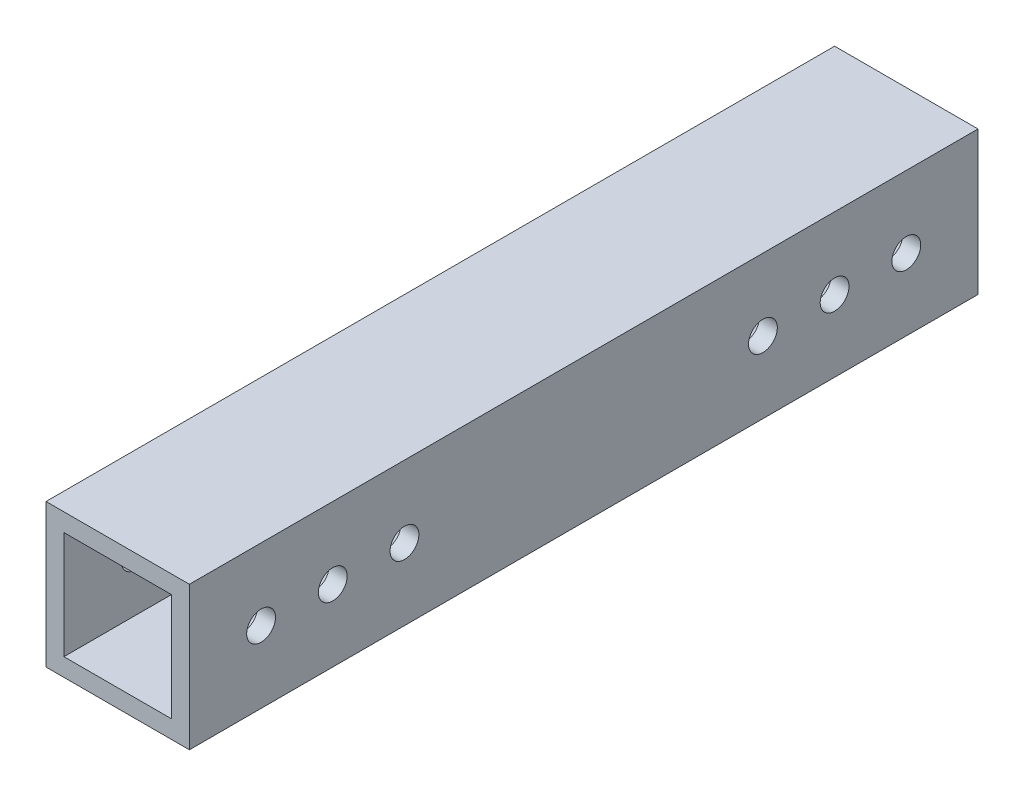
SolidWorks part; units mm, degrees
material "6061 Alloy"
ref_plane "Front" through (0, 0, 0) normal (0, 0, 1) x (1, 0, 0)
ref_plane "Top" through (0, 0, 0) normal (0, 1, 0) x (1, 0, 0)
ref_plane "Right" through (0, 0, 0) normal (1, 0, 0) x (0, 0, -1)
sketch "Sketch1" plane through (0, 0, 0) normal (0, 0, 1) x (1, 0, 0)
  line L1 (0, 0) -> (-25.4, 0)
  line L2 (0, 0) -> (0, 25.4)
  line L3 (0, 25.4) -> (-25.4, 25.4)
  line L4 (-25.4, 0) -> (-25.4, 25.4)
  dimension "D1" = 25.4
extrude "Extrude-Thin1" add sketch "Sketch1" along normal blind 139.7 thin
hole_wizard "#10 Clearance Hole1" positions "Sketch2" profile "Sketch3" hole size "#10" standard "ANSI Inch" end condition through all
sketch "Sketch2" plane through (0, 0, 0) normal (1, 0, 0) x (0, 0, -1)
  line L0 (0, 0) -> (0, 25.4) construction
  line L1 (-139.7, 0) -> (0, 0) construction
  point P0 (-12.7, 12.7)
  point P2 (-25.4, 12.7)
  point P4 (-38.1, 12.7)
  point P7 (0, 0)
  point P8 (0, 0)
  point P11 (0, 0)
  dimension "D1" = 12.7
  dimension "D2" = 12.7
  dimension "D3" = 12.7
  dimension "D4" = 12.7
sketch "Sketch3" plane through (0, 12.7, 12.7) normal (0, 1, 0) x (0, 0, -1)
  line L0 (0, 0) -> (0, 25.4)
  line L1 (0, 25.4) -> (2.5527, 25.4)
  line L2 (2.5527, 25.4) -> (2.5527, 0)
  line L5 (2.5527, 0) -> (0, 0)
  line L11 (0, -6.35) -> (0, 107.95) construction
  dimension "Thru Hole Dia." = 5.1054
  dimension "Thru Hole Depth" = 25.4
hole_wizard "#10 Clearance Hole2" positions "Sketch4" profile "Sketch5" hole size "#10" standard "ANSI Inch" end condition through all
sketch "Sketch4" plane through (-25.4, 0, 0) normal (-1, 0, 0) x (0, 0, 1)
  line L0 (139.7, 0) -> (0, 0) construction
  line L1 (139.7, 25.4) -> (139.7, 0) construction
  point P0 (114.3, 12.7)
  point P2 (127, 12.7)
  point P4 (101.6, 12.7)
  dimension "D1" = 12.7
  dimension "D2" = 12.7
  dimension "D3" = 12.7
  dimension "D4" = 12.7
sketch "Sketch5" plane through (-25.4, 12.7, 114.3) normal (0, 1, 0) x (0, 0, 1)
  line L0 (0, 0) -> (0, 25.4)
  line L1 (0, 25.4) -> (2.5527, 25.4)
  line L2 (2.5527, 25.4) -> (2.5527, 0)
  line L5 (2.5527, 0) -> (0, 0)
  line L11 (0, -6.35) -> (0, 107.95) construction
  dimension "Thru Hole Dia." = 5.1054
  dimension "Thru Hole Depth" = 25.4
